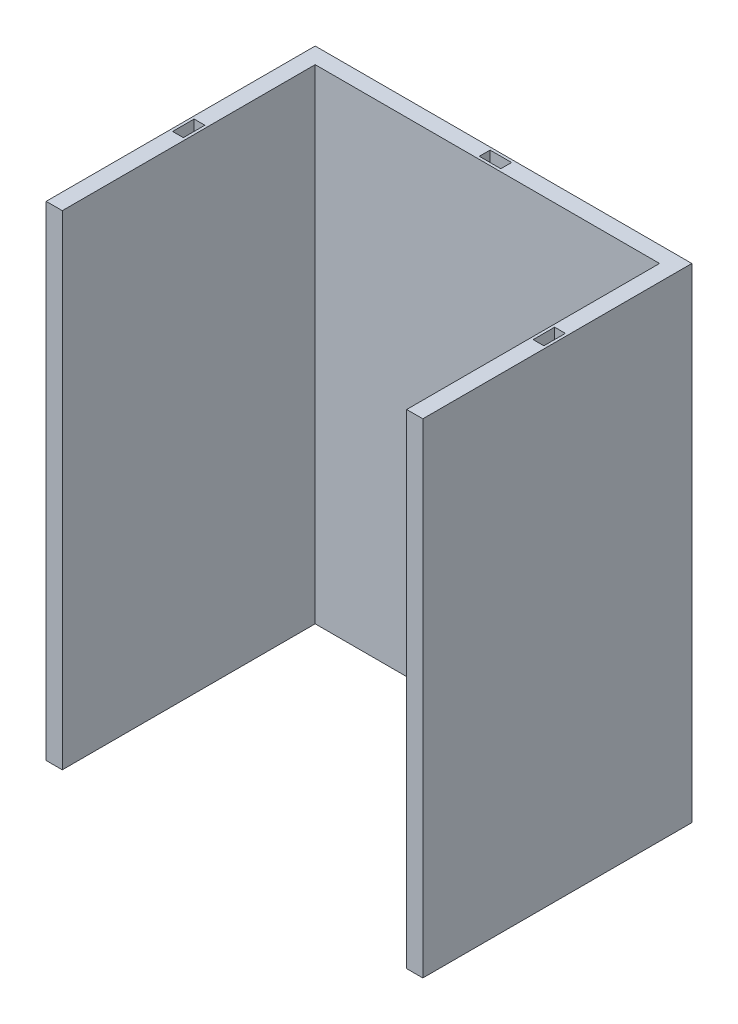
SolidWorks part; units mm, degrees
ref_plane "Front Plane" through (0, 0, 0) normal (0, 0, 1) x (1, 0, 0)
ref_plane "Top Plane" through (0, 0, 0) normal (0, 1, 0) x (1, 0, 0)
ref_plane "Right Plane" through (0, 0, 0) normal (1, 0, 0) x (0, 0, -1)
sketch "Sketch1" plane through (0, 0, 0) normal (0, 1, 0) x (1, 0, 0)
  line L0 (-35, 0) -> (-35, 50)
  line L1 (-35, 50) -> (35, 50)
  line L2 (35, 50) -> (35, 0)
  line L3 (-32, 0) -> (-32, 47)
  line L4 (-32, 47) -> (32, 47)
  line L5 (32, 47) -> (32, 0)
  line L6 (-35, 0) -> (-32, 0)
  line L7 (35, 0) -> (32, 0)
  point P2 (0, 50)
  point P5 (0, 0)
  dimension "D1" = 70
  dimension "D2" = 50
  dimension "D3" = 3
extrude "Boss-Extrude1" add sketch "Sketch1" along normal mid plane 90
sketch "Sketch2" plane through (0, 45, 0) normal (0, 1, 0) x (1, 0, 0)
  line L0 (-33.5, 0) -> (-33.5, 50) construction
  line L1 (-35, 0) -> (-32, 0) construction
  line L2 (35, 50) -> (-35, 50) construction
  line L3 (0, 0) -> (0, 50) construction
  line L4 (-35, 48.5) -> (35, 48.5) construction
  line L5 (-35, 50) -> (-35, 0) construction
  line L6 (35, 0) -> (35, 50) construction
  line L8 (34.5, 23) -> (32.5, 23)
  line L9 (-34.5, 27) -> (-32.5, 27)
  line L10 (-34.5, 27) -> (-34.5, 23)
  line L11 (-34.5, 23) -> (-32.5, 23)
  line L12 (-32.5, 27) -> (-32.5, 23)
  line L13 (-34.5, 27) -> (-32.5, 23) construction
  line L14 (-34.5, 23) -> (-32.5, 27) construction
  line L15 (-2, 49.5) -> (2, 49.5)
  line L16 (-2, 49.5) -> (-2, 47.5)
  line L17 (-2, 47.5) -> (2, 47.5)
  line L18 (2, 49.5) -> (2, 47.5)
  line L19 (-2, 49.5) -> (2, 47.5) construction
  line L20 (-2, 47.5) -> (2, 49.5) construction
  line L21 (32.5, 27) -> (32.5, 23)
  line L22 (34.5, 27) -> (32.5, 27)
  line L23 (34.5, 27) -> (34.5, 23)
  point P13 (0, 48.5)
  point P16 (-33.5, 25)
  dimension "D1" = 1.5
  dimension "D2" = 2
  dimension "D3" = 4
  dimension "D4" = 2
  dimension "D5" = 4
extrude "Cut-Extrude1" cut sketch "Sketch2" against normal blind 3
mirror "Mirror1" about plane through (0, 0, 0) normal (0, 1, 0) of "Cut-Extrude1"
